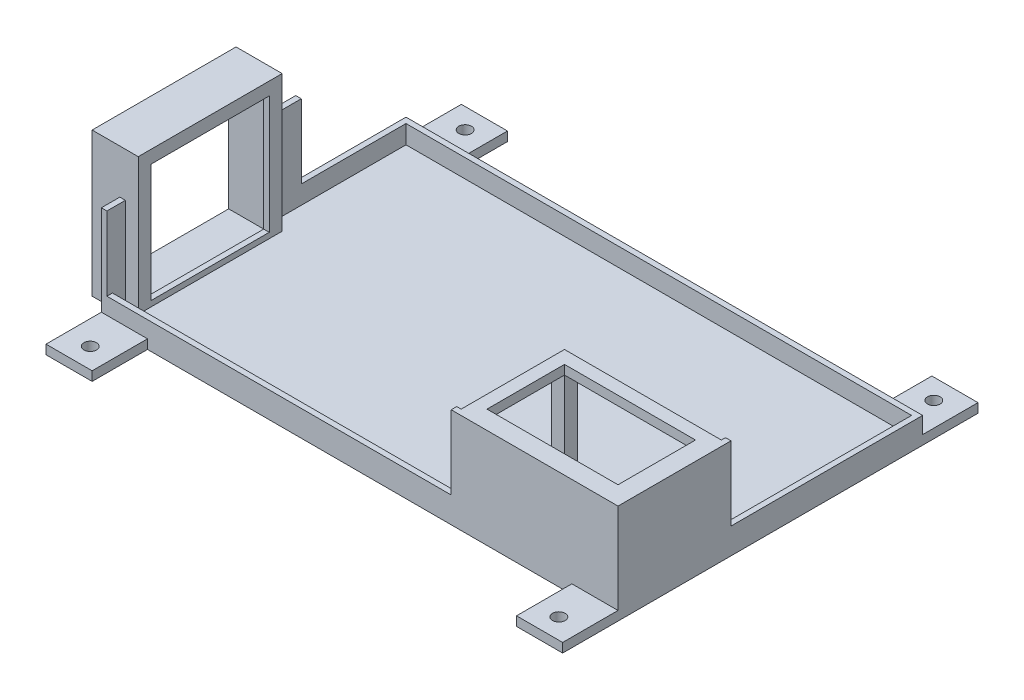
SolidWorks part; units mm, degrees
ref_plane "Front Plane" through (0, 0, 0) normal (0, 0, 1) x (1, 0, 0)
ref_plane "Top Plane" through (0, 0, 0) normal (0, 1, 0) x (1, 0, 0)
ref_plane "Right Plane" through (0, 0, 0) normal (1, 0, 0) x (0, 0, -1)
sketch "Sketch1" plane through (0, 0, 0) normal (0, 1, 0) x (1, 0, 0)
  line L1 (-140, -82.55) -> (140, -82.55)
  line L2 (-140, -82.55) -> (-140, 82.55)
  line L3 (-140, 82.55) -> (140, 82.55)
  line L4 (140, -82.55) -> (140, 82.55)
  line L5 (-140, -82.55) -> (140, 82.55) construction
  line L6 (-140, 82.55) -> (140, -82.55) construction
  point P0 (0, 0)
  dimension "D1" = 165.1
  dimension "D2" = 280
extrude "Floor" add sketch "Sketch1" along normal blind 4
sketch "Sketch2" plane through (0, 4, 0) normal (0, 1, 0) x (1, 0, 0)
  line L0 (137, -79.55) -> (137, 79.55)
  line L1 (137, 79.55) -> (-137, 79.55)
  line L2 (-137, 79.55) -> (-137, -79.55)
  line L3 (-137, -79.55) -> (137, -79.55)
  line L4 (140, -82.55) -> (140, 82.55)
  line L5 (140, 82.55) -> (-140, 82.55)
  line L6 (-140, 82.55) -> (-140, -82.55)
  line L7 (-140, -82.55) -> (140, -82.55)
  line L8 (140, -82.55) -> (140, 82.55)
  line L9 (140, 82.55) -> (-140, 82.55)
  line L10 (-140, 82.55) -> (-140, -82.55)
  line L11 (-140, -82.55) -> (140, -82.55)
  dimension "D1" = 0
  dimension "D2" = 3
extrude "Wall" add sketch "Sketch2" along normal blind 10
sketch "Sketch4" plane through (0, 4, 0) normal (0, 1, 0) x (1, 0, 0)
  line L0 (130, -30.55) -> (59, -30.55)
  line L1 (137, -79.55) -> (52, -79.55)
  line L2 (137, -79.55) -> (137, -23.55)
  line L3 (137, -23.55) -> (52, -23.55)
  line L4 (52, -79.55) -> (52, -23.55)
  line L5 (59, -72.55) -> (59, -30.55)
  line L6 (130, -72.55) -> (59, -72.55)
  line L7 (130, -72.55) -> (130, -30.55)
  dimension "D1" = 85
  dimension "D2" = 56
  dimension "D3" = 7
extrude "Rpi stand" add sketch "Sketch4" along normal blind 5 from offset 45
sketch "Sketch7" plane through (0, 14, 0) normal (0, 1, 0) x (1, 0, 0)
  line L0 (-137, 79.55) -> (-137, -79.55) construction
  line L1 (-140, -82.55) -> (-137, -82.55)
  line L2 (-140, -82.55) -> (-140, 22.7839)
  line L3 (-140, 22.7839) -> (-137, 22.7839)
  line L4 (-137, -82.55) -> (-137, 22.7839)
  line L5 (-137, -79.55) -> (137, -79.55) construction
  line L6 (140, -82.55) -> (49.6123, -82.55)
  line L7 (140, -82.55) -> (140, -79.55)
  line L8 (137, -79.55) -> (49.6123, -79.55)
  line L9 (49.6123, -82.55) -> (49.6123, -79.55)
  line L10 (137, -79.55) -> (137, 79.55) construction
  line L12 (140, -79.55) -> (140, -21.3069)
  line L13 (140, -21.3069) -> (137, -21.3069)
  line L14 (137, -79.55) -> (137, -21.3069)
  line L15 (-137, -79.55) -> (137, -79.55) construction
  point P19 (137, -21.3069)
  point P20 (49.6123, -79.55)
extrude "Temp support" add sketch "Sketch7" along normal blind 40
sketch "Sketch3" plane through (0, 0, 0) normal (0, 1, 0) x (1, 0, 0)
  line L0 (-127, 101.6) -> (127, 101.6) construction
  line L1 (-140, 82.55) -> (-115, 82.55)
  line L2 (-140, 82.55) -> (-140, 112.55)
  line L3 (-140, 112.55) -> (-115, 112.55)
  line L4 (-115, 82.55) -> (-115, 112.55)
  line L5 (140, 82.55) -> (115, 82.55)
  line L6 (140, 82.55) -> (140, 112.55)
  line L7 (140, 112.55) -> (115, 112.55)
  line L8 (115, 82.55) -> (115, 112.55)
  line L9 (-140, -82.55) -> (-115, -82.55)
  line L10 (-140, -82.55) -> (-140, -112.55)
  line L11 (-140, -112.55) -> (-115, -112.55)
  line L12 (-115, -82.55) -> (-115, -112.55)
  line L13 (140, -82.55) -> (115, -82.55)
  line L14 (140, -82.55) -> (140, -112.55)
  line L15 (140, -112.55) -> (115, -112.55)
  line L16 (115, -82.55) -> (115, -112.55)
  line L17 (127, 101.6) -> (127, -101.6) construction
  line L18 (127, -101.6) -> (-127, -101.6) construction
  line L19 (-127, -101.6) -> (-127, 101.6) construction
  line L20 (-140, 30.6215) -> (140, 30.6215) construction
  line L22 (140, -21.3069) -> (140, 82.55) construction
  line L23 (0, 101.6) -> (0, -101.6) construction
  line L24 (-140, 22.7839) -> (-140, -82.55) construction
  line L25 (140, -21.3069) -> (140, 82.55) construction
  line L26 (-137, -82.55) -> (49.6123, -82.55) construction
  circle A0 centre (-127, 101.6) radius 3.429
  circle A1 centre (127, 101.6) radius 3.429
  circle A2 centre (127, -101.6) radius 3.429
  circle A3 centre (-127, -101.6) radius 3.429
  point P28 (-127.5, -82.55)
  point P29 (-115, -97.55)
  point P30 (127.5, -82.55)
  point P31 (-115, 97.55)
  point P34 (0, 0)
  point P35 (-140, -82.55)
  point P36 (-140, 0)
  point P39 (-140, 0)
  dimension "D5" = 6.858
  dimension "D1" = 25
  dimension "D2" = 25
  dimension "D3" = 30
  dimension "D4" = 30
  dimension "D6" = 203.2
  dimension "D7" = 254
extrude "Brackets" add sketch "Sketch3" along normal blind 5
sketch "Sketch5" plane through (-140, 0, 0) normal (-1, 0, 0) x (0, 0, 1)
  line L0 (-5.45, 78) -> (72.55, 78)
  line L1 (-1.45, 4) -> (68.55, 4)
  line L2 (-1.45, 4) -> (-1.45, 74)
  line L3 (-1.45, 74) -> (68.55, 74)
  line L4 (68.55, 4) -> (68.55, 74)
  line L5 (72.55, 0) -> (72.55, 78)
  line L6 (-5.45, 0) -> (72.55, 0)
  line L7 (-5.45, 0) -> (-5.45, 78)
  line L9 (112.55, 5) -> (112.55, 0) construction
  line L11 (-79.55, 4) -> (79.55, 4) construction
  dimension "D1" = 70
  dimension "D2" = 70
  dimension "D5" = 40
  dimension "D3" = 4
extrude "Fan Holder" add sketch "Sketch5" along normal blind 15 and the other way blind 10 contours L3 L4 L1 L2
sketch "Sketch8" plane through (-140, 0, 0) normal (-1, 0, 0) x (0, 0, 1)
  line L4 (-1.45, 54) -> (-1.45, 4)
  line L5 (-1.45, 4) -> (68.55, 4)
  line L6 (68.55, 4) -> (68.55, 54)
  line L7 (68.55, 54) -> (-1.45, 54)
  line L8 (-1.45, 54) -> (-1.45, 4)
  line L9 (-1.45, 4) -> (68.55, 4)
  line L10 (68.55, 4) -> (68.55, 54)
  line L15 (68.55, 54) -> (-1.45, 54)
  dimension "D1" = 0
extrude "Fan hole" cut sketch "Sketch8" against normal up to next (3 mm away)
sketch "Sketch11" plane through (-130, 0, 0) normal (-1, 0, 0) x (0, 0, 1)
  line L4 (-5.45, 78) -> (-5.45, 0)
  line L5 (-5.45, 0) -> (72.55, 0)
  line L6 (72.55, 0) -> (72.55, 78)
  line L7 (72.55, 78) -> (-5.45, 78)
  line L8 (-5.45, 78) -> (-5.45, 0)
  line L9 (-5.45, 0) -> (72.55, 0)
  line L10 (72.55, 0) -> (72.55, 78)
  line L11 (72.55, 78) -> (-5.45, 78)
  line L16 (1.55, 71) -> (1.55, 7)
  line L17 (1.55, 7) -> (65.55, 7)
  line L18 (65.55, 7) -> (65.55, 71)
  line L19 (65.55, 71) -> (1.55, 71)
  line L20 (1.55, 71) -> (1.55, 7)
  line L21 (1.55, 7) -> (65.55, 7)
  line L22 (65.55, 7) -> (65.55, 71)
  line L23 (65.55, 71) -> (1.55, 71)
  dimension "D1" = 0
  dimension "D2" = 7
extrude "Boss-Extrude9" add sketch "Sketch11" along normal blind 3
sketch "Sketch12" plane through (0, 49, 0) normal (0, -1, 0) x (1, 0, 0)
  line L1 (52, 23.55) -> (59, 23.55)
  line L2 (52, 23.55) -> (52, 30.55)
  line L3 (52, 30.55) -> (59, 30.55)
  line L4 (59, 23.55) -> (59, 30.55)
  dimension "D1" = 7
  dimension "D2" = 7
extrude "Boss-Extrude10" add sketch "Sketch12" along normal up to next
equation "\"D2@Sketch3\"=\"D1@Sketch3\""
equation "\"D4@Sketch3\"=\"D3@Sketch3\""
